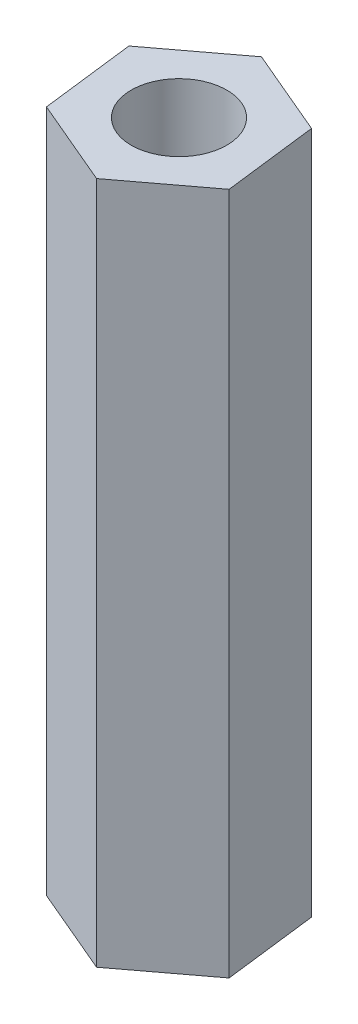
SolidWorks part; units mm, degrees
material "黄铜"
ref_plane "前视基准面" through (0, 0, 0) normal (0, 0, 1) x (1, 0, 0)
ref_plane "上视基准面" through (0, 0, 0) normal (0, 1, 0) x (1, 0, 0)
ref_plane "右视基准面" through (0, 0, 0) normal (1, 0, 0) x (0, 0, -1)
sketch "草图1" plane through (0, 0, 0) normal (0, 1, 0) x (1, 0, 0)
  line L1 (3.3206, 2.5007) -> (-0.5054, 4.1261)
  line L2 (-0.5054, 4.1261) -> (-3.826, 1.6254)
  line L3 (-3.826, 1.6254) -> (-3.3206, -2.5007)
  line L4 (-3.3206, -2.5007) -> (0.5054, -4.1261)
  line L5 (0.5054, -4.1261) -> (3.826, -1.6254)
  line L6 (3.826, -1.6254) -> (3.3206, 2.5007)
  circle A0 centre (0, 0) radius 2.1
  circle A1 centre (0, 0) radius 3.6 construction
  dimension "D1" = 4.2
  dimension "D2" = 1.5
extrude "凸台-拉伸1" add sketch "草图1" along normal blind 30
